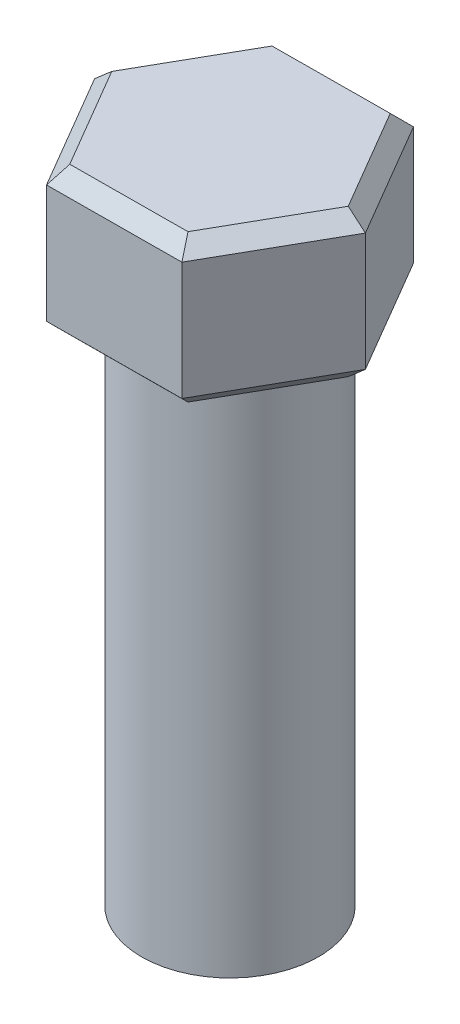
SolidWorks part; units mm, degrees
material "Acero al carbono no aleado"
ref_plane "Alzado" through (0, 0, 0) normal (0, 0, 1) x (1, 0, 0)
ref_plane "Planta" through (0, 0, 0) normal (0, 1, 0) x (1, 0, 0)
ref_plane "Vista lateral" through (0, 0, 0) normal (1, 0, 0) x (0, 0, -1)
sketch "Croquis2" plane through (0, 0, 0) normal (0, 1, 0) x (1, 0, 0)
  circle A0 centre (0, 0) radius 6
extrude "Saliente-Extruir1" add sketch "Croquis2" along normal blind 35
sketch "Croquis3" plane through (0, 35, 0) normal (0, 1, 0) x (1, 0, 0)
  line L1 (4.6078, -7.8663) -> (9.1163, 0.0574)
  line L2 (9.1163, 0.0574) -> (4.5085, 7.9236)
  line L3 (4.5085, 7.9236) -> (-4.6078, 7.8663)
  line L4 (-4.6078, 7.8663) -> (-9.1163, -0.0574)
  line L5 (-9.1163, -0.0574) -> (-4.5085, -7.9236)
  line L6 (-4.5085, -7.9236) -> (4.6078, -7.8663)
  circle A0 centre (0, 0) radius 7.8951 construction
extrude "Saliente-Extruir2" add sketch "Croquis3" along normal blind 10
chamfer "Chaflán1" distance 1 angle 45 12 edges at (6.8621, 35, 3.9045) (6.8124, 35, -3.9905) (-0.0497, 35, -7.895) (-6.8621, 35, -3.9045) (-6.8124, 35, 3.9905) (0.0497, 35, 7.895) (-6.8621, 45, -3.9045) (-0.0497, 45, -7.895) (6.8124, 45, -3.9905) (6.8621, 45, 3.9045) (0.0497, 45, 7.895) (-6.8124, 45, 3.9905)
